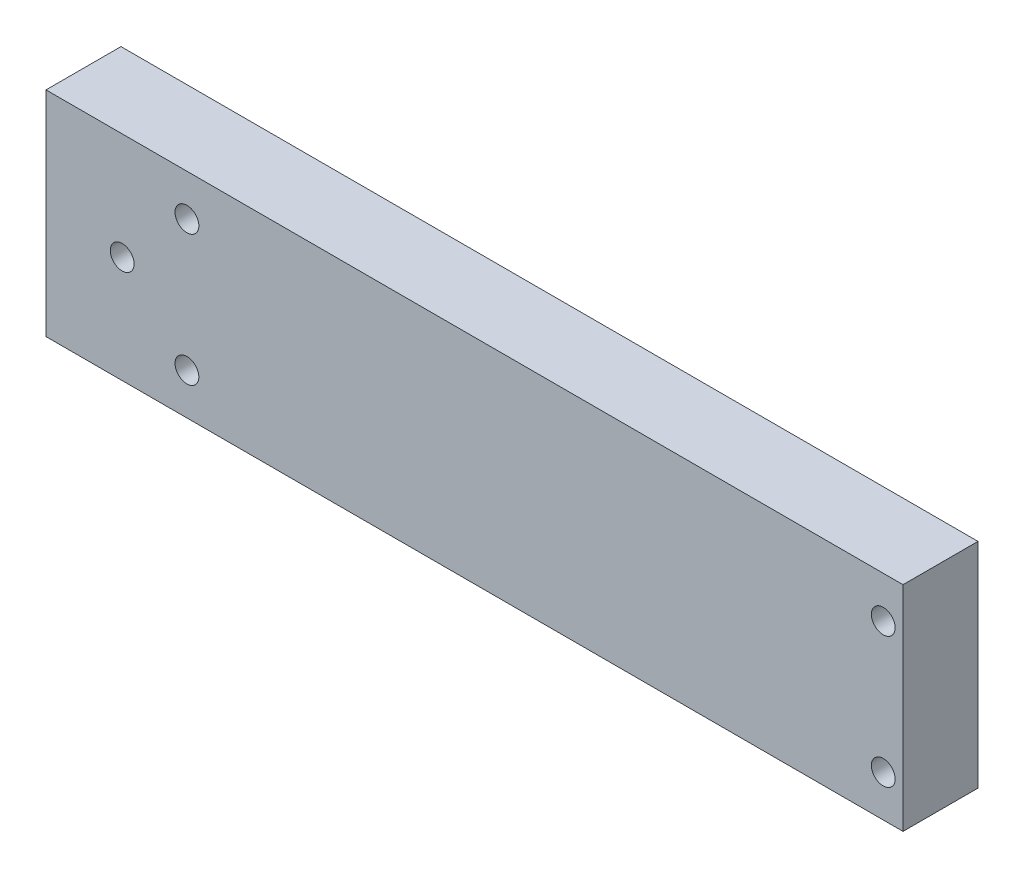
SolidWorks part; units mm, degrees
ref_plane "정면" through (0, 0, 0) normal (0, 0, 1) x (1, 0, 0)
ref_plane "윗면" through (0, 0, 0) normal (0, 1, 0) x (1, 0, 0)
ref_plane "우측면" through (0, 0, 0) normal (1, 0, 0) x (0, 0, -1)
sketch "스케치1" plane through (0, 0, 0) normal (0, 0, 1) x (1, 0, 0)
  line L1 (0, 0) -> (114.3, 0)
  line L2 (0, 0) -> (0, 28.5)
  line L3 (0, 28.5) -> (114.3, 28.5)
  line L4 (114.3, 0) -> (114.3, 28.5)
  dimension "D1" = 28.5
  dimension "D2" = 114.3
extrude "보스-돌출1" add sketch "스케치1" along normal blind 10
hole_wizard "구멍1" positions "스케치4" profile "스케치5" legacy end condition through all
sketch "스케치4" plane through (0, 0, 10) normal (0, 0, 1) x (1, 0, 0)
  line L0 (0, 28.5) -> (0, 0) construction
  line L1 (0, 14.25) -> (130.1055, 14.25) construction
  point P0 (18.796, 22.9813)
  point P4 (111.665, 22.9813)
  point P7 (10.16, 14.25)
  point P14 (0, 0)
  point P15 (0, 0)
  point P16 (0, 0)
  point P17 (0, 0)
  point P18 (16.2198, 22.133)
  point P21 (0, 0)
  point P22 (0, 0)
  dimension "D1" = 10.16
  dimension "D2" = 8.636
  dimension "D3" = 92.869
  dimension "D4" = 17.4625
sketch "스케치5" plane through (18.796, 22.9813, 10) normal (1, 0, 0) x (0, -1, 0)
  line L0 (0, 0) -> (0, 10)
  line L1 (0, 10) -> (1.5875, 10)
  line L2 (1.5875, 10) -> (1.5875, 0)
  line L3 (1.5875, 0) -> (0, 0)
  line L4 (0, 110) -> (0, -10) construction
  dimension "지름" = 3.175
  dimension "깊이" = 10
ref_plane "평면1" through (0, 14.25, 0) normal (0, 1, 0) x (1, 0, 0)
mirror "대칭 복사1" about plane through (0, 14.25, 0) normal (0, 1, 0) of "구멍1"
